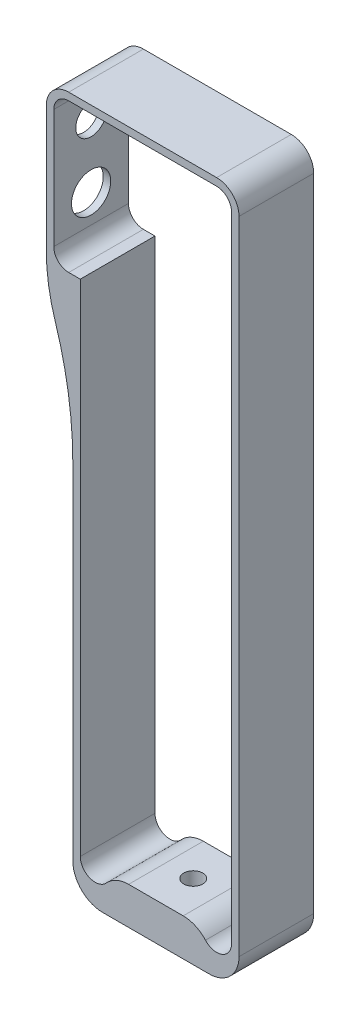
SolidWorks part; units mm, degrees
material "Сплав 2024"
ref_plane "Спереди" through (0, 0, 0) normal (0, 0, 1) x (1, 0, 0)
ref_plane "Сверху" through (0, 0, 0) normal (0, 1, 0) x (1, 0, 0)
ref_plane "Справа" through (0, 0, 0) normal (1, 0, 0) x (0, 0, -1)
sketch "Эскиз1" plane through (0, 0, 0) normal (0, 0, 1) x (1, 0, 0)
  line L0 (-2, -10) -> (42.5, -10)
  line L1 (8, 0) -> (32.5, 0)
  line L2 (0, 0) -> (0, 170)
  line L3 (0, 170) -> (40.5, 170)
  line L4 (40.5, 0) -> (40.5, 170)
  line L5 (42.5, -10) -> (42.5, 172)
  line L6 (-2, 172) -> (42.5, 172)
  line L7 (-2, -10) -> (-2, 172)
  arc A0 (0, 0) -> (8, 0) centre (4, 0) ccw
  arc A1 (32.5, 0) -> (40.5, 0) centre (36.5, 0) ccw
  dimension "D6" = 8
  dimension "D7" = 8
  dimension "D1" = 40.5
  dimension "D2" = 170
  dimension "D3" = 10
  dimension "D4" = 2
  dimension "D5" = 2
  dimension "D8" = 2
extrude "Бобышка-Вытянуть1" add sketch "Эскиз1" along normal blind 20
fillet "Скругление1" radius 8 4 edges at (42.5, -10, 10) (-2, -10, 10) (32.5, 0, 10) (8, 0, 10)
sketch "Эскиз2" plane through (0, -10, 0) normal (0, -1, 0) x (1, 0, 0)
  line L0 (20.25, 20) -> (20.25, 0) construction
  line L1 (6, 20) -> (34.5, 20) construction
  line L2 (6, 0) -> (34.5, 0) construction
  line L3 (34.5, 10) -> (6, 10) construction
  line L4 (34.5, 0) -> (34.5, 20) construction
  line L5 (6, 20) -> (6, 0) construction
hole_wizard "Отверстие обработанное метчиком 1/4-201" positions "Эскиз4" profile "Эскиз3" tap size "1/4-20" standard "Ansi Inch"
sketch "Эскиз4" plane through (0, -10, 0) normal (0, -1, 0) x (-1, 0, 0)
  line L0 (-20.25, -20) -> (-20.25, 0) construction
  point P0 (-20.25, -10)
sketch "Эскиз3" plane through (20.25, -10, 10) normal (1, 0, 0) x (0, 0, -1)
  line L0 (0, 0) -> (0, 10)
  line L1 (0, 10) -> (2.5527, 10)
  line L2 (2.5527, 10) -> (2.5527, 0)
  line L5 (2.5527, 0) -> (0, 0)
  line L11 (0, -6.35) -> (0, 107.95) construction
  dimension "Диаметр проходного сверла" = 5.1054
  dimension "Глубина проходного сверла" = 10
cosmetic thread "Отверстие резьбы1" parameters "D2"=6.35
ref_plane "Плоскость1" through (0, 155, 0) normal (0, 1, 0) x (1, 0, 0)
sketch "Эскиз5" plane through (0, 0, 20) normal (0, 0, 1) x (1, 0, 0)
  line L0 (-7.1, 155) -> (-7.1, 132.6982) construction
  line L2 (-7.1, 155) -> (-7.1, 136)
  line L3 (17.5494, 155) -> (-17.5494, 155) construction
  line L4 (0, 170) -> (0, 0) construction
  line L5 (-9.1, 155) -> (-9.1, 136)
  line L6 (-2, 110.3175) -> (-2, 114.4689)
  line L7 (-2, 172) -> (-2, -2) construction
  line L8 (-9.1, 155) -> (-7.1, 155)
  arc A0 (-9.1, 136) -> (-2, 110.3175) centre (40.9, 136) ccw
  arc A1 (-7.1, 136) -> (-2, 114.4689) centre (40.9, 136) ccw
  dimension "D4" = 100
  dimension "D1" = 7.1
  dimension "D2" = 19
  dimension "D3" = 2
extrude "Бобышка-Вытянуть2" add sketch "Эскиз5" against normal up to surface (20 mm away) up to face at (20.25, 52.781, 0)
fillet "Скругление2" radius 100 1 edges at (-2, 110.3175, 10)
sketch "Эскиз6" plane through (0, 0, 20) normal (0, 0, 1) x (1, 0, 0)
  line L2 (0, 170) -> (0, 114.4689)
  line L3 (0, 114.4689) -> (-2, 114.4689)
  line L4 (-2, 170) -> (-2, 114.4689)
  line L5 (42.5, 172) -> (-2, 172)
  line L6 (42.5, 172) -> (42.5, 170)
  line L7 (42.5, 170) -> (0, 170)
  line L8 (-2, 172) -> (-2, 170)
extrude "Вырез-Вытянуть1" cut sketch "Эскиз6" against normal up to next
sketch "Эскиз7" plane through (-9.1, 0, 0) normal (-1, 0, 0) x (0, 0, 1)
  line L0 (10, 155) -> (10, 133.3641) construction
  line L1 (0, 155) -> (20, 155) construction
  circle A0 centre (10, 145.4263) radius 5.25
  dimension "D1" = 10.5
extrude "Вырез-Вытянуть2" cut sketch "Эскиз7" against normal up to next
sketch "Эскиз9" plane through (0, 0, 20) normal (0, 0, 1) x (1, 0, 0)
  line L0 (-7.052, 133.8533) -> (0, 133.8533)
  line L1 (0, 133.8533) -> (0, 114.4689)
  line L2 (-2, 114.4689) -> (0, 114.4689) construction
  line L3 (-2, 114.4689) -> (0, 114.4689)
  arc A0 (-7.1, 136) -> (-2, 114.4689) centre (40.9, 136) ccw construction
  arc A1 (-7.052, 133.8533) -> (-2, 114.4689) centre (40.9, 136) ccw
extrude "Бобышка-Вытянуть3" add sketch "Эскиз9" against normal up to surface (20 mm away) up to face at (12.0849, 66.2873, 0)
fillet "Скругление7" radius 4 1 edges at (-7.052, 133.8533, 10)
sketch "Эскиз10" plane through (0, 0, 20) normal (0, 0, 1) x (1, 0, 0)
  line L0 (17.5494, 155) -> (-17.5494, 155) construction
  line L1 (-9.1, 155) -> (-7.1, 155)
  line L2 (-9.1, 155) -> (-9.1, 172.1367)
  line L3 (-9.1, 172.1367) -> (-7.1, 172.1367)
  line L4 (-7.1, 155) -> (-7.1, 172.1367)
  line L5 (-9.1, 155) -> (-9.1, 136) construction
extrude "Бобышка-Вытянуть4" add sketch "Эскиз10" against normal up to surface (20 mm away) up to face at (12.0513, 68.2919, 0)
sketch "Эскиз11" plane through (-9.1, 0, 0) normal (-1, 0, 0) x (0, 0, 1)
  line L0 (10, 145.4263) -> (10, 162.0459) construction
  circle A0 centre (10, 162.4263) radius 4.1
  dimension "D1" = 8.2
  dimension "D2" = 17
extrude "Вырез-Вытянуть3" cut sketch "Эскиз11" against normal up to next
fillet "Скругление9" [suppressed] radius 0.2
sketch "Эскиз12" plane through (0, 0, 20) normal (0, 0, 1) x (1, 0, 0)
  line L1 (42.5, 169.6552) -> (-9.1, 169.6552)
  line L2 (42.5, 169.6552) -> (42.5, 172.1367)
  line L3 (42.5, 172.1367) -> (-9.1, 172.1367)
  line L4 (-9.1, 169.6552) -> (-9.1, 172.1367)
extrude "Вырез-Вытянуть4" cut sketch "Эскиз12" against normal up to next
sketch "Эскиз13" plane through (0, 0, 20) normal (0, 0, 1) x (1, 0, 0)
  line L0 (36.5, 175.6552) -> (-3.1, 175.6552)
  line L1 (40.5, 0) -> (40.5, 169.6552) construction
  line L2 (-7.1, 137.8533) -> (-7.1, 169.6552) construction
  line L3 (40.5, 0) -> (40.5, 169.6552) construction
  line L4 (-7.1, 169.6552) -> (-9.1, 169.6552)
  line L5 (42.5, 169.6552) -> (40.5, 169.6552)
  line L6 (-3.1, 173.6552) -> (36.5, 173.6552)
  line L7 (42.5, -2) -> (42.5, 169.6552) construction
  arc A0 (40.5, 169.6552) -> (36.5, 173.6552) centre (36.5, 169.6552) ccw
  arc A1 (-9.1, 169.6552) -> (-3.1, 175.6552) centre (-3.1, 169.6552) cw
  arc A2 (42.5, 169.6552) -> (36.5, 175.6552) centre (36.5, 169.6552) ccw
  arc A4 (-7.1, 169.6552) -> (-3.1, 173.6552) centre (-3.1, 169.6552) cw
  dimension "D1" = 4
  dimension "D2" = 4
extrude "Бобышка-Вытянуть5" add sketch "Эскиз13" against normal up to surface (20 mm away) up to face at (12.0513, 69.723, 0)
ref_plane "Плоскость2" through (20.25, 0, 0) normal (1, 0, 0) x (0, 0, -1)
ref_plane "Плоскость3" through (0, 0, 10) normal (0, 0, 1) x (1, 0, 0)
equation "\"D1@Эскиз5\"=5.5+1.6"
